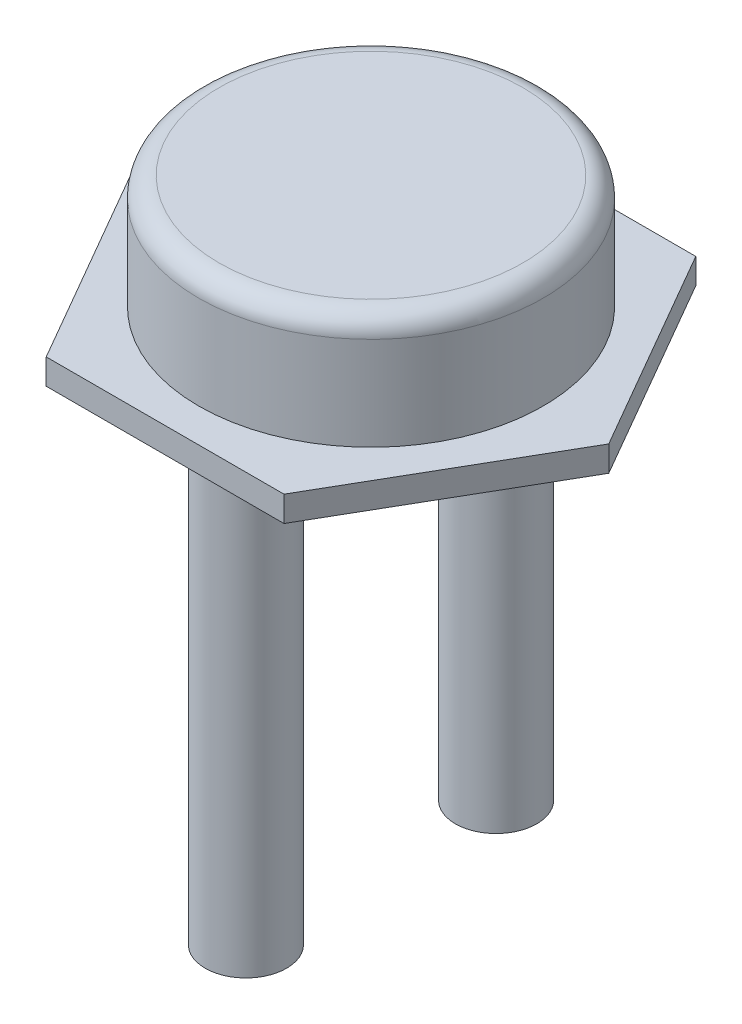
SolidWorks part; units mm, degrees
ref_plane "Front Plane" through (0, 0, 0) normal (0, 0, 1) x (1, 0, 0)
ref_plane "Top Plane" through (0, 0, 0) normal (0, 1, 0) x (1, 0, 0)
ref_plane "Right Plane" through (0, 0, 0) normal (1, 0, 0) x (0, 0, -1)
sketch "Sketch1" plane through (0, 0, 0) normal (0, 1, 0) x (1, 0, 0)
  circle A0 centre (0, 0) radius 10.75
  dimension "D1" = 21.5
extrude "Boss-Extrude1" add sketch "Sketch1" along normal blind 7.1
sketch "Sketch2" plane through (0, 0, 0) normal (0, -1, 0) x (1, 0, 0)
  line L1 (-14.8379, 0) -> (-7.419, -12.85)
  line L2 (-7.419, -12.85) -> (7.419, -12.85)
  line L3 (7.419, -12.85) -> (14.8379, 0)
  line L4 (14.8379, 0) -> (7.419, 12.85)
  line L5 (7.419, 12.85) -> (-7.419, 12.85)
  line L6 (-7.419, 12.85) -> (-14.8379, 0)
  circle A0 centre (0, 0) radius 12.85 construction
  dimension "D1" = 25.7
extrude "Boss-Extrude2" add sketch "Sketch2" along normal blind 1.5875
sketch "Sketch3" plane through (0, -1.5875, 0) normal (0, -1, 0) x (1, 0, 0)
  line L0 (0, 7.8066) -> (0, -7.8066) construction
  circle A0 centre (0, 7.8066) radius 2.54
  circle A1 centre (0, -7.8066) radius 2.54
  point P4 (0, 0)
  dimension "D1" = 5.08
extrude "Boss-Extrude3" add sketch "Sketch3" along normal blind 29
fillet "Fillet1" radius 1.27 1 edges at (0, 7.1, 10.75)
